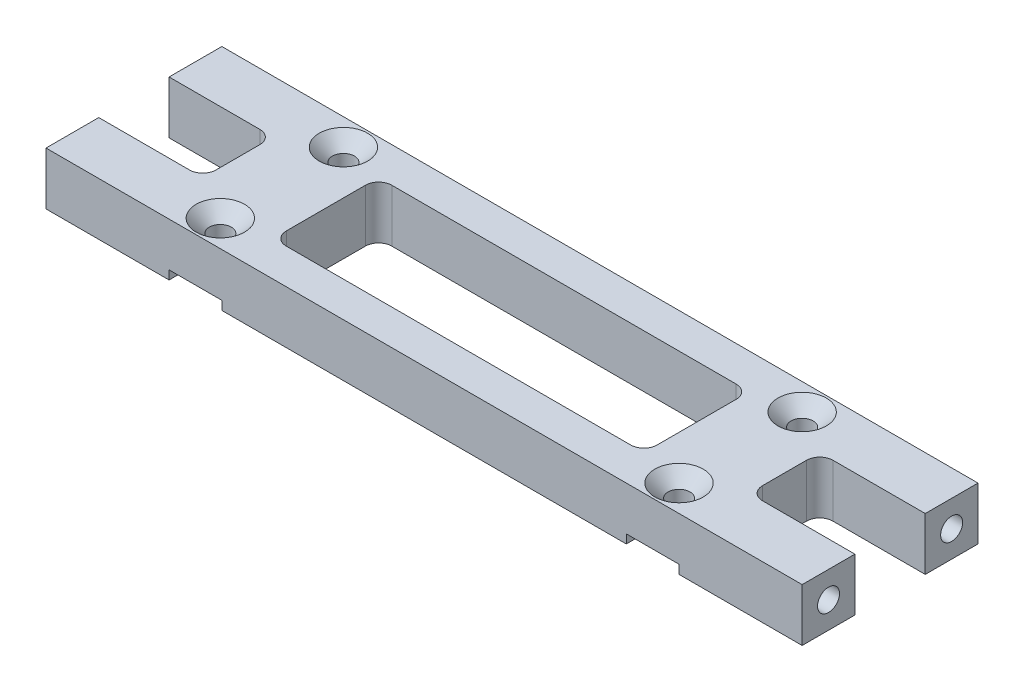
SolidWorks part; units mm, degrees
material "1060 Alloy"
ref_plane "Front Plane" through (0, 0, 0) normal (0, 0, 1) x (1, 0, 0)
ref_plane "Top Plane" through (0, 0, 0) normal (0, 1, 0) x (1, 0, 0)
ref_plane "Right Plane" through (0, 0, 0) normal (1, 0, 0) x (0, 0, -1)
sketch "Sketch2" plane through (0, 0, 0) normal (0, 1, 0) x (1, 0, 0)
  line L1 (86, -20) -> (0, -20)
  line L5 (0, -20) -> (0, 0)
  line L6 (86, -20) -> (86, 0)
  line L11 (86, 0) -> (0, 0)
  dimension "D2" = 86
  dimension "D9" = 20
extrude "Boss-Extrude1" add sketch "Sketch2" along normal blind 6
hole_wizard "Tap Drill for M3 Tap2" positions "Sketch6" profile "Sketch5" hole size "M3" standard "ISO"
sketch "Sketch6" plane through (86, 0.7792, 7.6405) normal (1, 0, 0) x (0, 0, -1)
  line L4 (-12.3595, -0.7792) -> (7.6405, -0.7792) construction
  line L6 (-12.3595, 5.2208) -> (-12.3595, -0.7792) construction
  line L7 (7.6405, 5.2208) -> (7.6405, -0.7792) construction
  point P0 (-9.3595, 2.2208)
  point P2 (4.6405, 2.2208)
  dimension "D1" = 3
  dimension "D2" = 3
  dimension "D3" = 3
sketch "Sketch5" plane through (86, 3, 17) normal (0, 1, 0) x (0, 0, -1)
  line L0 (0, 0) -> (0, 8.7511)
  line L1 (0, 8.7511) -> (1.25, 8)
  line L2 (1.25, 8) -> (1.25, 0)
  line L5 (1.25, 0) -> (0, 0)
  line L10 (0, 8.7511) -> (-1.25, 8) construction
  line L11 (0, -6.35) -> (0, 107.95) construction
  dimension "Hole Dia." = 2.5
  dimension "Hole Depth" = 8
  dimension "Drill Angle" = 118
hole_wizard "Tap Drill for M3 Tap1" positions "Sketch4" profile "Sketch3" hole size "M3" standard "ISO"
sketch "Sketch4" plane through (0, 0, 0) normal (-1, 0, 0) x (0, 0, 1)
  line L0 (0, 0) -> (20, 0) construction
  line L2 (0, 6) -> (0, 0) construction
  line L3 (20, 6) -> (20, 0) construction
  point P0 (3, 3)
  point P2 (17, 3)
  dimension "D1" = 3
  dimension "D2" = 3
  dimension "D3" = 3
sketch "Sketch3" plane through (0, 3, 3) normal (0, 1, 0) x (0, 0, 1)
  line L0 (0, 0) -> (0, 8.7511)
  line L1 (0, 8.7511) -> (1.25, 8)
  line L2 (1.25, 8) -> (1.25, 0)
  line L5 (1.25, 0) -> (0, 0)
  line L10 (0, 8.7511) -> (-1.25, 8) construction
  line L11 (0, -6.35) -> (0, 107.95) construction
  dimension "Hole Dia." = 2.5
  dimension "Hole Depth" = 8
  dimension "Drill Angle" = 118
sketch "Sketch7" plane through (0, 0, 0) normal (0, -1, 0) x (1, 0, 0)
  line L0 (0, 20) -> (86, 20) construction
  line L1 (14, 20) -> (20, 20)
  line L2 (14, 20) -> (14, 0)
  line L3 (14, 0) -> (20, 0)
  line L4 (20, 20) -> (20, 0)
  line L5 (86, 0) -> (0, 0) construction
  line L6 (0, 0) -> (0, 20) construction
  line L7 (72, 20) -> (66, 20)
  line L8 (72, 20) -> (72, 0)
  line L9 (72, 0) -> (66, 0)
  line L10 (66, 20) -> (66, 0)
  line L11 (86, 20) -> (86, 0) construction
  dimension "D1" = 14
  dimension "D2" = 6
  dimension "D3" = 14
extrude "Cut-Extrude1" cut sketch "Sketch7" against normal blind 1
hole_wizard "Tap Drill for M3x0.5 Tap1" positions "3DSketch1" profile "Sketch8" hole size "M3x0.5" standard "ANSI Metric" end condition up to next
sketch3d "3DSketch1"
  line L0 (72, 1, 0) -> (72, 1, 20) construction
  line L1 (66, 1, 0) -> (72, 1, 0) construction
  line L2 (20, 1, 20) -> (14, 1, 20) construction
  line L3 (14, 0, 20) -> (14, 0, 0) construction
  point P0 (16.8284, 1, 17)
  point P2 (16.8284, 1, 3)
  point P4 (69, 1, 17)
  point P6 (69, 1, 3)
  dimension "D1" = 3
  dimension "D2" = 3
  dimension "D3" = 3
  dimension "D4" = 3
sketch "Sketch8" plane through (16.8284, 1, 17) normal (1, 0, 0) x (0, 0, -1)
  line L0 (0, 0) -> (0, 5)
  line L1 (0, 5) -> (1.25, 5)
  line L2 (1.25, 5) -> (1.25, 0)
  line L5 (1.25, 0) -> (0, 0)
  line L11 (0, -6.35) -> (0, 107.95) construction
  dimension "Thru Hole Dia." = 2.5
  dimension "Thru Hole Depth" = 5
chamfer "Chamfer1" distance 1.5 angle 45 4 edges at (16.8284, 6, 15.75) (16.8284, 6, 1.75) (69, 6, 15.75) (69, 6, 1.75)
sketch "Sketch9" plane through (0, 6, 0) normal (0, 1, 0) x (1, 0, 0)
  line L0 (86, 0) -> (0, 0) construction
  line L1 (21.8284, -4) -> (64, -4)
  line L2 (21.8284, -4) -> (21.8284, -16)
  line L3 (21.8284, -16) -> (64, -16)
  line L4 (64, -4) -> (64, -16)
  line L5 (0, -20) -> (86, -20) construction
  line L6 (0, 0) -> (0, -20) construction
  line L7 (0, -6) -> (11.8284, -6)
  line L8 (0, -6) -> (0, -14)
  line L9 (0, -14) -> (11.8284, -14)
  line L10 (11.8284, -6) -> (11.8284, -14)
  line L11 (86, -20) -> (86, 0) construction
  line L12 (86, -6) -> (74, -6)
  line L13 (86, -6) -> (86, -14)
  line L14 (86, -14) -> (74, -14)
  line L15 (74, -6) -> (74, -14)
  circle A0 centre (16.8284, -17) radius 1.25 construction
  circle A1 centre (69, -3) radius 1.25 construction
  circle A2 centre (16.8284, -3) radius 1.25 construction
  dimension "D1" = 5
  dimension "D2" = 5
  dimension "D5" = 5
  dimension "D8" = 5
  dimension "D3" = 4
  dimension "D4" = 4
  dimension "D6" = 6
  dimension "D7" = 6
  dimension "D9" = 6
  dimension "D10" = 6
extrude "Cut-Extrude2" cut sketch "Sketch9" against normal up to next
fillet "Fillet1" radius 1.5 8 edges at (74, 3, 14) (74, 3, 6) (21.8284, 3, 16) (21.8284, 3, 4) (64, 3, 16) (64, 3, 4) (11.8284, 3, 14) (11.8284, 3, 6)
